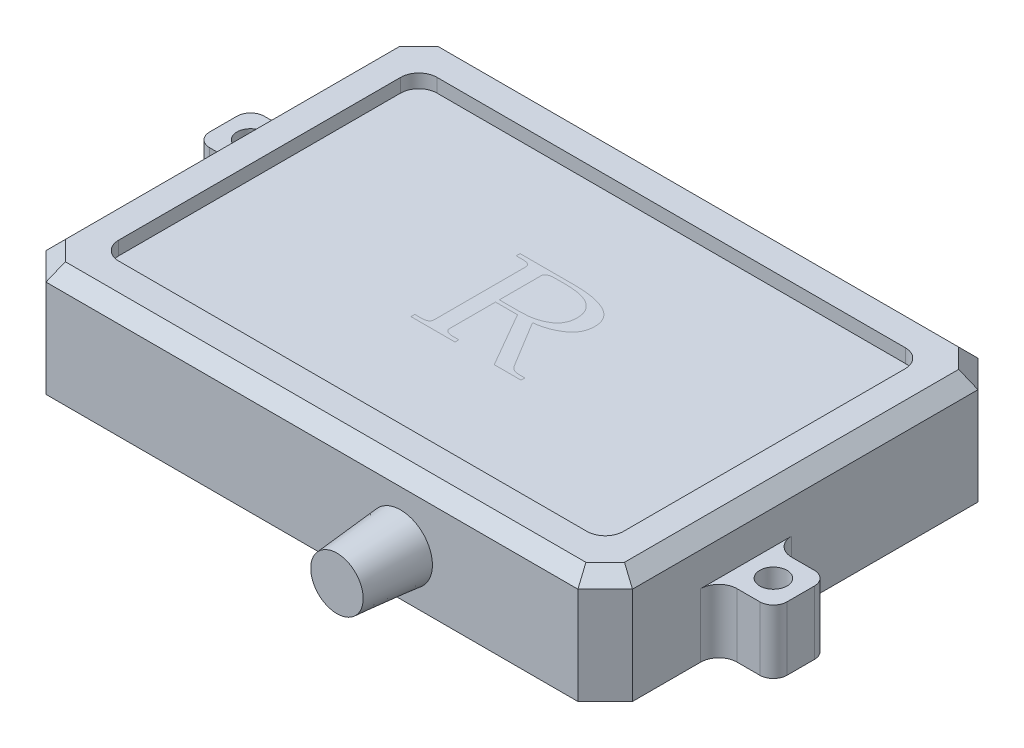
SolidWorks part; units mm, degrees
ref_plane "前视基准面" through (0, 0, 0) normal (0, 0, 1) x (1, 0, 0)
ref_plane "上视基准面" through (0, 0, 0) normal (0, 1, 0) x (1, 0, 0)
ref_plane "右视基准面" through (0, 0, 0) normal (1, 0, 0) x (0, 0, -1)
sketch "草图1" plane through (0, 0, 0) normal (0, 1, 0) x (1, 0, 0)
  line L0 (-32.25, 19) -> (-29.25, 22)
  line L1 (-29.25, -22) -> (29.25, -22)
  line L2 (-32.25, -19) -> (-32.25, 19)
  line L3 (-29.25, 22) -> (29.25, 22)
  line L4 (32.25, -19) -> (32.25, 19)
  line L5 (-32.25, -22) -> (32.25, 22) construction
  line L6 (-32.25, 22) -> (32.25, -22) construction
  line L7 (-32.25, -19) -> (-29.25, -22)
  line L8 (29.25, -22) -> (32.25, -19)
  line L9 (29.25, 22) -> (32.25, 19)
  point P0 (0, 0)
  dimension "D1" = 44
  dimension "D2" = 64.5
extrude "凸台-拉伸1" add sketch "草图1" along normal blind 12.2
chamfer "倒角1" distance 1.5 angle 45 8 edges at (-30.75, 12.2, -20.5) (0, 12.2, -22) (30.75, 12.2, -20.5) (32.25, 12.2, 0) (30.75, 12.2, 20.5) (0, 12.2, 22) (-30.75, 12.2, 20.5) (-32.25, 12.2, 0)
sketch "草图2" plane through (0, 12.2, 0) normal (0, 1, 0) x (1, 0, 0)
  line L0 (32.25, 19) -> (32.25, -19) construction
  line L1 (-25.75, 17.5) -> (25.75, 17.5)
  line L2 (-27.75, 15.5) -> (-27.75, -15.5)
  line L3 (-25.75, -17.5) -> (25.75, -17.5)
  line L4 (27.75, 15.5) -> (27.75, -15.5)
  line L5 (-29.25, 22) -> (29.25, 22) construction
  line L6 (-32.25, -19) -> (-32.25, 19) construction
  line L7 (29.25, -22) -> (-29.25, -22) construction
  arc A0 (-25.75, 17.5) -> (-27.75, 15.5) centre (-25.75, 15.5) ccw
  arc A1 (-27.75, -15.5) -> (-25.75, -17.5) centre (-25.75, -15.5) ccw
  arc A2 (25.75, -17.5) -> (27.75, -15.5) centre (25.75, -15.5) ccw
  arc A3 (25.75, 17.5) -> (27.75, 15.5) centre (25.75, 15.5) cw
  dimension "D5" = 2
  dimension "D1" = 4.5
  dimension "D2" = 4.5
  dimension "D3" = 4.5
  dimension "D4" = 4.5
extrude "切除-拉伸1" cut sketch "草图2" against normal blind 1.5
sketch "草图3" plane through (0, 0, 0) normal (0, -1, 0) x (1, 0, 0)
  line L0 (32.25, 9.5) -> (36.75, 9.5)
  line L1 (32.25, 19) -> (32.25, -19) construction
  line L2 (38.25, 8) -> (38.25, 5)
  line L3 (36.75, 3.5) -> (32.25, 3.5)
  line L4 (-32.25, -19) -> (-32.25, 19) construction
  line L5 (-29.25, 22) -> (29.25, 22) construction
  line L6 (-32.25, -3.5) -> (-36.75, -3.5)
  line L7 (-38.25, -5) -> (-38.25, -8)
  line L8 (-36.75, -9.5) -> (-32.25, -9.5)
  line L9 (29.25, -22) -> (-29.25, -22) construction
  line L10 (32.25, 9.5) -> (32.25, 3.5)
  line L11 (-32.25, -3.5) -> (-32.25, -9.5)
  circle A0 centre (35.25, 6.5) radius 1.5
  circle A1 centre (-35.25, -6.5) radius 1.5
  arc A2 (36.75, 9.5) -> (38.25, 8) centre (36.75, 8) cw
  arc A3 (38.25, 5) -> (36.75, 3.5) centre (36.75, 5) cw
  arc A4 (-36.75, -3.5) -> (-38.25, -5) centre (-36.75, -5) ccw
  arc A5 (-38.25, -8) -> (-36.75, -9.5) centre (-36.75, -8) ccw
  point P15 (38.25, 6.5)
  point P29 (-38.25, -6.5)
  dimension "D1" = 3
  dimension "D3" = 1.5
  dimension "D5" = 15.5
  dimension "D6" = 15.5
  dimension "D7" = 3
  dimension "D8" = 3
  dimension "D2" = 6
  dimension "D4" = 70.5
extrude "凸台-拉伸2" add sketch "草图3" against normal blind 7
fillet "圆角1" radius 2 4 edges at (-32.25, 3.5, -9.5) (-32.25, 3.5, -3.5) (32.25, 3.5, 3.5) (32.25, 3.5, 9.5)
sketch "草图4" plane through (0, 0, 22) normal (0, 0, 1) x (1, 0, 0)
  line L0 (32.25, 10.7) -> (32.25, 0) construction
  line L1 (-29.25, 0) -> (29.25, 0) construction
  circle A0 centre (9.75, 5) radius 3.5
  dimension "D1" = 7
  dimension "D2" = 22.5
  dimension "D3" = 5
extrude "凸台-拉伸3" add sketch "草图4" along normal blind 7 draft 5
sketch "草图5" plane through (0, 0, -22) normal (0, 0, -1) x (-1, 0, 0)
  line L0 (-32.25, 10.7) -> (-32.25, 0) construction
  line L1 (-29.25, 0) -> (29.25, 0) construction
  line L2 (-23.25, 4) -> (-23.25, 0)
  line L3 (-23.25, 0) -> (2.75, 0)
  line L4 (2.75, 0) -> (2.75, 4)
  line L5 (-6.25, 4) -> (-5.25, 4)
  line L6 (-15.25, 4) -> (-14.25, 4)
  line L7 (32.25, 10.7) -> (32.25, 0) construction
  line L8 (9.25, 9) -> (17.25, 9)
  line L9 (9.25, 9) -> (9.25, 0)
  line L10 (9.25, 0) -> (17.25, 0)
  line L11 (17.25, 9) -> (17.25, 0)
  arc A0 (-15.25, 4) -> (-23.25, 4) centre (-19.25, 4) ccw
  arc A1 (-6.25, 4) -> (-14.25, 4) centre (-10.25, 4) ccw
  arc A2 (2.75, 4) -> (-5.25, 4) centre (-1.25, 4) ccw
  dimension "D1" = 13
  dimension "D2" = 9
  dimension "D3" = 9
  dimension "D4" = 4
  dimension "D5" = 8
  dimension "D6" = 15
  dimension "D7" = 8
  dimension "D8" = 9
extrude "切除-拉伸2" cut sketch "草图5" against normal blind 2
sketch "草图6" plane through (0, 0, -20) normal (0, 0, -1) x (-1, 0, 0)
  line L0 (17.25, 9) -> (9.25, 9) construction
  line L1 (10.25, 8) -> (16.25, 8)
  line L2 (10.25, 8) -> (10.25, 6.5)
  line L3 (10.25, 6.5) -> (16.25, 6.5)
  line L4 (16.25, 8) -> (16.25, 6.5)
  line L5 (17.25, 0) -> (17.25, 9) construction
  circle A0 centre (-19.25, 4) radius 2
  circle A1 centre (-10.25, 4) radius 2
  circle A2 centre (-1.25, 4) radius 2
  point P15 (0, 0)
  point P17 (0, 0)
  point P19 (10.4939, 7.9842)
  point P20 (16.0445, 7.8488)
  point P21 (13.25, 8)
  point P22 (13.25, 9)
  dimension "D1" = 4
  dimension "D2" = 2.5
  dimension "D3" = 1
  dimension "D4" = 1
extrude "切除-拉伸3" cut sketch "草图6" against normal blind 3
sketch "草图7" plane through (0, 10.7, 0) normal (0, 1, 0) x (1, 0, 0)
  line L0 (-27.75, -5.5) -> (27.75, -5.5) construction
  line L1 (-27.75, 15.5) -> (-27.75, -15.5) construction
  line L2 (27.75, -15.5) -> (27.75, 15.5) construction
  line L3 (-25.75, -17.5) -> (25.75, -17.5) construction
  text T0 "R" font "宋体" height 12
  point P9 (-14.0275, 2.9837)
  dimension "D1" = 12
split line "分割线1"
sketch "草图8" plane through (0, 0, -20) normal (0, 0, -1) x (-1, 0, 0)
  line L5 (9.25, 4.5) -> (17.25, 4.5)
  line L6 (9.25, 9) -> (9.25, 0) construction
  line L7 (17.25, 0) -> (17.25, 9) construction
  line L8 (9.25, 0) -> (17.25, 0) construction
  circle A16 centre (-19.25, 4) radius 3
  circle A17 centre (-19.25, 4) radius 3
  circle A19 centre (-10.25, 4) radius 3
  circle A20 centre (-10.25, 4) radius 3
  circle A22 centre (-1.25, 4) radius 3
  circle A23 centre (-1.25, 4) radius 3
  dimension "D4" = 4.5
  dimension "D1" = 1
  dimension "D2" = 1
  dimension "D3" = 1
split line "分割线2"
